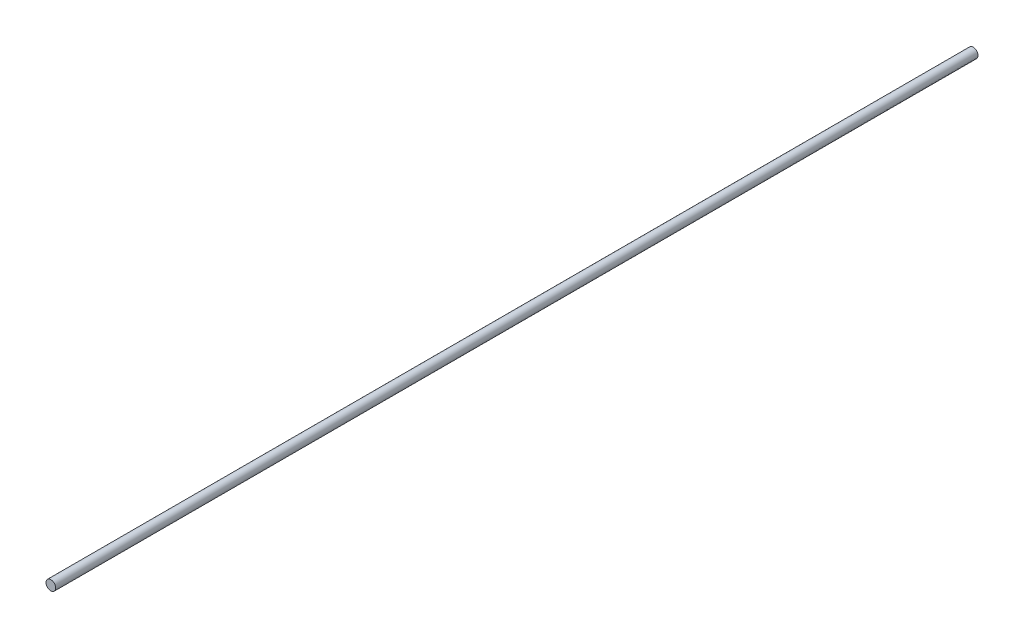
SolidWorks part; units mm, degrees
ref_plane "Plan de face" through (0, 0, 0) normal (0, 0, 1) x (1, 0, 0)
ref_plane "Plan de dessus" through (0, 0, 0) normal (0, 1, 0) x (1, 0, 0)
ref_plane "Plan de droite" through (0, 0, 0) normal (1, 0, 0) x (0, 0, -1)
sketch "Esquisse1" plane through (0, 0, 0) normal (0, 0, 1) x (1, 0, 0)
  circle A0 centre (0, 0) radius 1
  dimension "D1" = 2
extrude "Boss.-Extru.1" add sketch "Esquisse1" along normal blind 190
